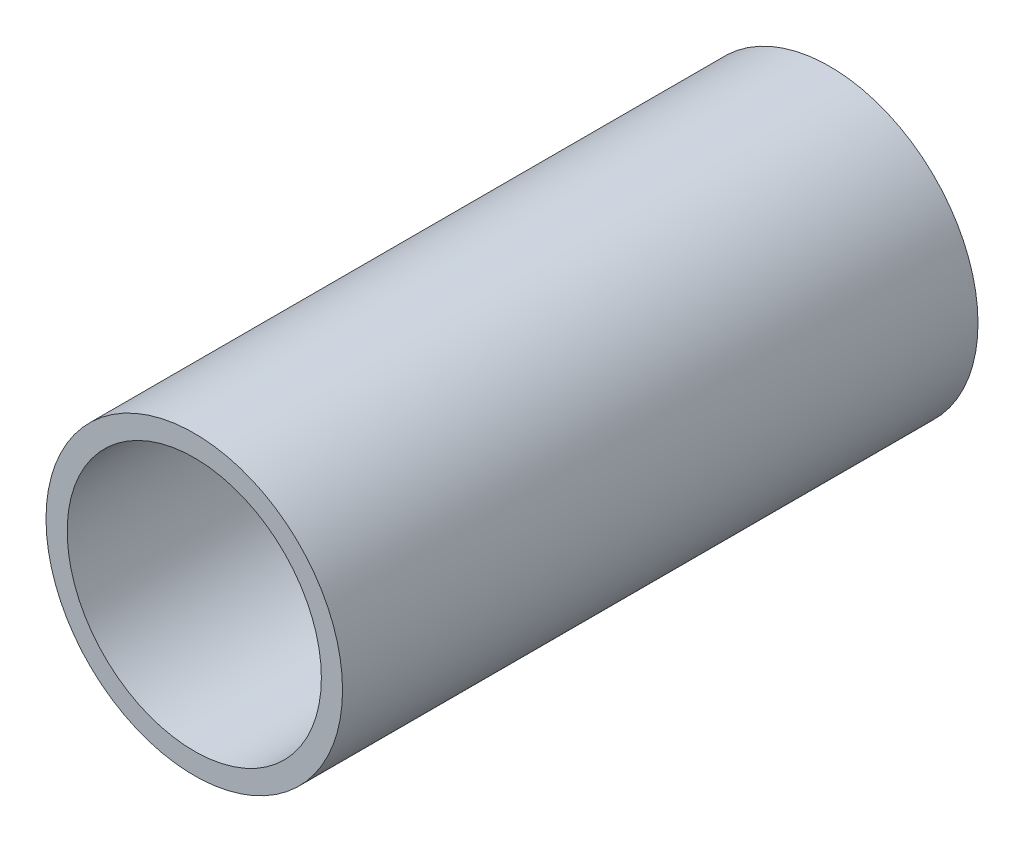
SolidWorks part; units mm, degrees
ref_plane "Front Plane" through (0, 0, 0) normal (0, 0, 1) x (1, 0, 0)
ref_plane "Top Plane" through (0, 0, 0) normal (0, 1, 0) x (1, 0, 0)
ref_plane "Right Plane" through (0, 0, 0) normal (1, 0, 0) x (0, 0, -1)
sketch "Sketch1" plane through (0, 0, 0) normal (0, 0, 1) x (1, 0, 0)
  circle A0 centre (0, 0) radius 3.5
extrude "Boss-Extrude1" add sketch "Sketch1" along normal blind 15
sketch "Sketch2" plane through (0, 0, 15) normal (0, 0, 1) x (1, 0, 0)
  circle A0 centre (0, 0) radius 3
extrude "Cut-Extrude1" cut sketch "Sketch2" against normal blind 15
